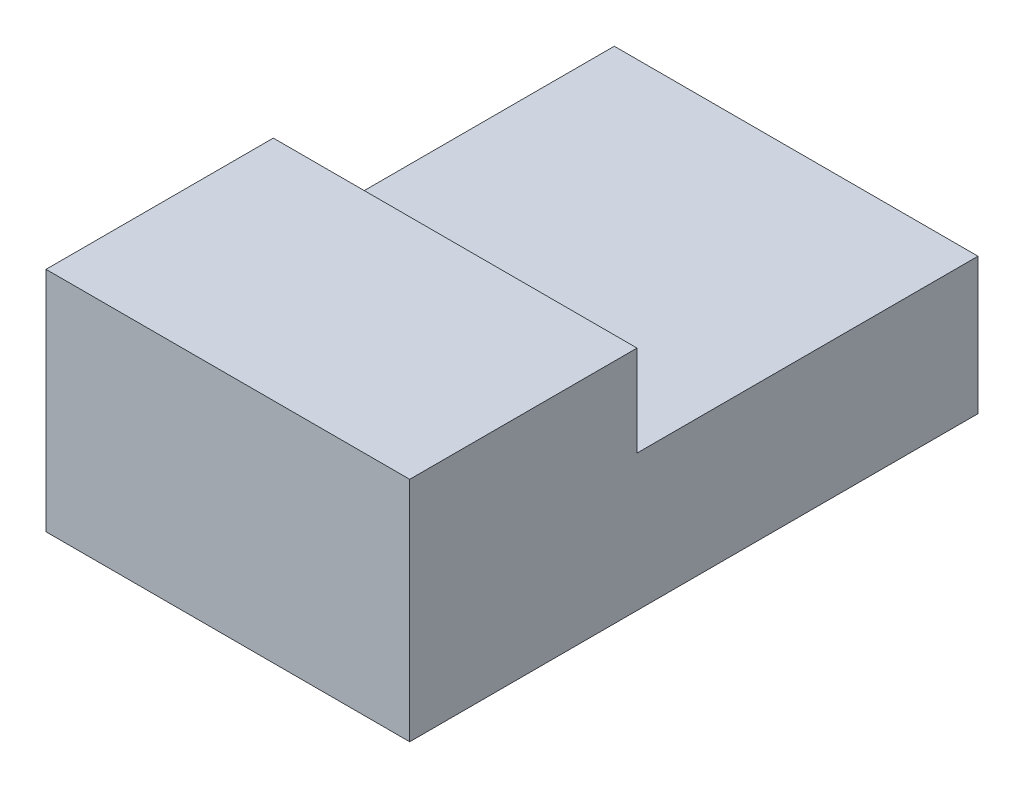
SolidWorks part; units mm, degrees
ref_plane "Ön Düzlem" through (0, 0, 0) normal (0, 0, 1) x (1, 0, 0)
ref_plane "Üst Düzlem" through (0, 0, 0) normal (0, 1, 0) x (1, 0, 0)
ref_plane "Sağ Düzlem" through (0, 0, 0) normal (1, 0, 0) x (0, 0, -1)
sketch "Çizim7" plane through (0, 0, 0) normal (1, 0, 0) x (0, 0, -1)
  line L0 (0, 0) -> (0, 100)
  line L1 (0, 100) -> (100, 100)
  line L2 (100, 100) -> (100, 60)
  line L3 (100, 60) -> (250, 60)
  line L4 (250, 60) -> (250, 0)
  line L5 (250, 0) -> (0, 0)
  dimension "D1" = 250
  dimension "D2" = 60
  dimension "D3" = 100
  dimension "D4" = 100
extrude "Yükseklik-Ekstrüzyon5" add sketch "Çizim7" along normal blind 160
sketch "Çizim8" plane through (0, 0, -100) normal (0, 0, -1) x (-1, 0, 0)
  line L0 (-160, 60) -> (-160, 100) construction
  line L1 (-157.3, 97.3) -> (-2.7, 97.3)
  line L2 (-157.3, 97.3) -> (-157.3, 60)
  line L3 (-157.3, 60) -> (-2.7, 60)
  line L4 (-2.7, 97.3) -> (-2.7, 60)
  line L5 (-160, 100) -> (0, 100) construction
  line L6 (0, 60) -> (0, 100) construction
  line L7 (-160, 60) -> (0, 60) construction
  dimension "D1" = 2.7
  dimension "D2" = 2.7
  dimension "D3" = 2.7
  dimension "D4" = 0
extrude "Kes-Ekstrüzyon4" cut sketch "Çizim8" against normal blind 97.3
